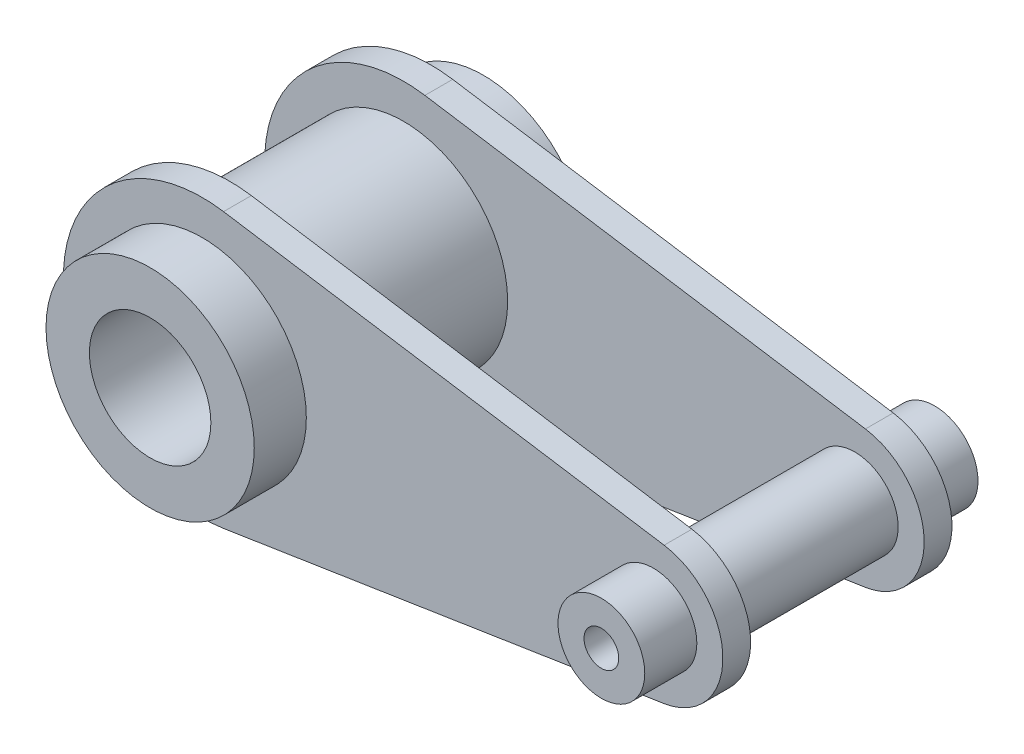
SolidWorks part; units mm, degrees
ref_plane "Front Plane" through (0, 0, 0) normal (0, 0, 1) x (1, 0, 0)
ref_plane "Top Plane" through (0, 0, 0) normal (0, 1, 0) x (1, 0, 0)
ref_plane "Right Plane" through (0, 0, 0) normal (1, 0, 0) x (0, 0, -1)
sketch "Sketch1" plane through (0, 0, 0) normal (0, 0, 1) x (1, 0, 0)
  line L0 (-65, 0) -> (65, 0) construction
  circle A0 centre (-65, 0) radius 30
  circle A1 centre (-65, 0) radius 17.5
  circle A2 centre (65, 0) radius 5
  circle A3 centre (65, 0) radius 12.5
  point P7 (0, 0)
  dimension "D1" = 60
  dimension "D2" = 35
  dimension "D3" = 25
  dimension "D4" = 10
  dimension "D5" = 130
extrude "Boss-Extrude1" add sketch "Sketch1" along normal mid plane 96
ref_plane "Plane1" through (0, 0, 33) normal (0, 0, 1) x (1, 0, 0)
sketch "Sketch2" plane through (0, 0, 33) normal (0, 0, 1) x (1, 0, 0)
  line L0 (68.0769, -19.7619) -> (-58.8462, -39.5238)
  line L1 (68.0769, 19.7619) -> (-58.8462, 39.5238)
  line L2 (-65, 0) -> (65, 0) construction
  arc A0 (-58.8462, 39.5238) -> (-58.8462, -39.5238) centre (-65, 0) ccw
  arc A1 (68.0769, -19.7619) -> (68.0769, 19.7619) centre (65, 0) ccw
  circle A2 centre (-65, 0) radius 30 construction
  circle A3 centre (-65, 0) radius 30
  circle A4 centre (65, 0) radius 12.5 construction
  circle A5 centre (65, 0) radius 12.5
  dimension "D1" = 80
  dimension "D2" = 40
extrude "Boss-Extrude2" add sketch "Sketch2" against normal blind 8
mirror "Mirror1" about plane through (0, 0, 0) normal (0, 0, 1) of "Boss-Extrude2"
